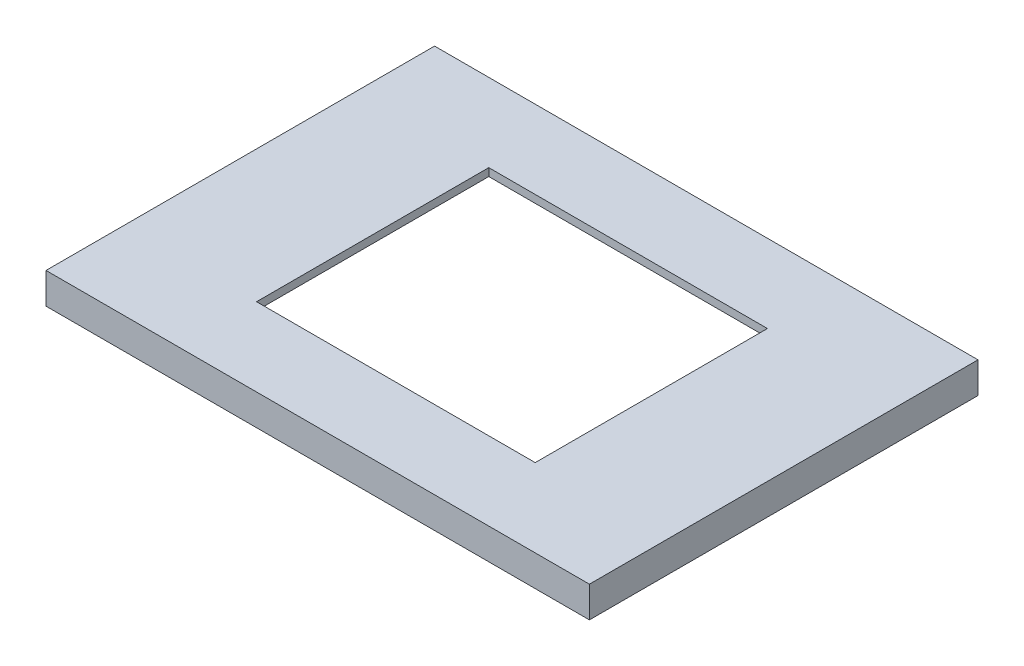
SolidWorks part; units mm, degrees
ref_plane "Front Plane" through (0, 0, 0) normal (0, 0, 1) x (1, 0, 0)
ref_plane "Top Plane" through (0, 0, 0) normal (0, 1, 0) x (1, 0, 0)
ref_plane "Right Plane" through (0, 0, 0) normal (1, 0, 0) x (0, 0, -1)
sketch "Sketch1" plane through (0, 0, 0) normal (0, 1, 0) x (1, 0, 0)
  line L0 (35.1, -25.1) -> (35.1, 25.1)
  line L1 (33.1, -23.1) -> (-33.1, -23.1)
  line L2 (33.1, -23.1) -> (33.1, 23.1)
  line L3 (33.1, 23.1) -> (-33.1, 23.1)
  line L4 (-33.1, -23.1) -> (-33.1, 23.1)
  line L5 (33.1, -23.1) -> (-33.1, 23.1) construction
  line L6 (33.1, 23.1) -> (-33.1, -23.1) construction
  line L7 (35.1, 25.1) -> (-35.1, 25.1)
  line L8 (-35.1, -25.1) -> (-35.1, 25.1)
  line L9 (35.1, -25.1) -> (-35.1, -25.1)
  point P0 (0, 0)
  dimension "D1" = 46.2
  dimension "D2" = 66.2
  dimension "D3" = 2
extrude "Boss-Extrude1" add sketch "Sketch1" along normal blind 1.25
sketch "Sketch2" plane through (0, 1.25, 0) normal (0, 1, 0) x (1, 0, 0)
  line L1 (-18, -15) -> (18, -15)
  line L2 (-18, -15) -> (-18, 15)
  line L3 (-18, 15) -> (18, 15)
  line L4 (18, -15) -> (18, 15)
  line L5 (-18, -15) -> (18, 15) construction
  line L6 (-18, 15) -> (18, -15) construction
  line L7 (35.1, -25.1) -> (-35.1, -25.1)
  line L8 (35.1, -25.1) -> (35.1, 25.1)
  line L9 (35.1, 25.1) -> (-35.1, 25.1)
  line L10 (-35.1, -25.1) -> (-35.1, 25.1)
  line L11 (35.1, -25.1) -> (-35.1, 25.1) construction
  line L12 (35.1, 25.1) -> (-35.1, -25.1) construction
  point P0 (0, 0)
  point P6 (0, 0)
  dimension "D1" = 36
  dimension "D2" = 30
extrude "Boss-Extrude2" add sketch "Sketch2" along normal blind 1
sketch "Sketch15" plane through (0, 0, 0) normal (0, -1, 0) x (1, 0, 0)
  line L1 (-35.1, 25.1) -> (35.1, 25.1)
  line L2 (-35.1, 25.1) -> (-35.1, -25.1)
  line L3 (-35.1, -25.1) -> (35.1, -25.1)
  line L4 (35.1, 25.1) -> (35.1, -25.1)
  line L9 (-33.1, 23.1) -> (33.1, 23.1)
  line L10 (-33.1, 23.1) -> (-33.1, -23.1)
  line L11 (-33.1, -23.1) -> (33.1, -23.1)
  line L12 (33.1, 23.1) -> (33.1, -23.1)
extrude "Boss-Extrude3" add sketch "Sketch15" along normal blind 1.75 contours L2 L1 L4 L3
ref_plane "Plane2" through (0, 0.05, 0) normal (0, -1, 0) x (-1, 0, 0)
ref_plane "Plane3" through (0, -0.85, 0) normal (0, -1, 0) x (-1, 0, 0)
sketch "Sketch3" plane through (0, -0.85, 0) normal (0, -1, 0) x (-1, 0, 0)
  line L1 (-33.1, 23.1) -> (33.1, 23.1)
  line L2 (-33.1, 23.1) -> (-33.1, -23.1)
  line L3 (-33.1, -23.1) -> (33.1, -23.1)
  line L4 (33.1, 23.1) -> (33.1, -23.1)
sweep "Cut-Sweep2" cut path "Sketch3" circular profile diameter 1 parameters "D3"=1
fillet "Fillet2" radius 0.1 4 edges at (-33.1, -0.35, 0) (0, -0.35, 23.1) (0, -0.35, -23.1) (33.1, -0.35, 0)
